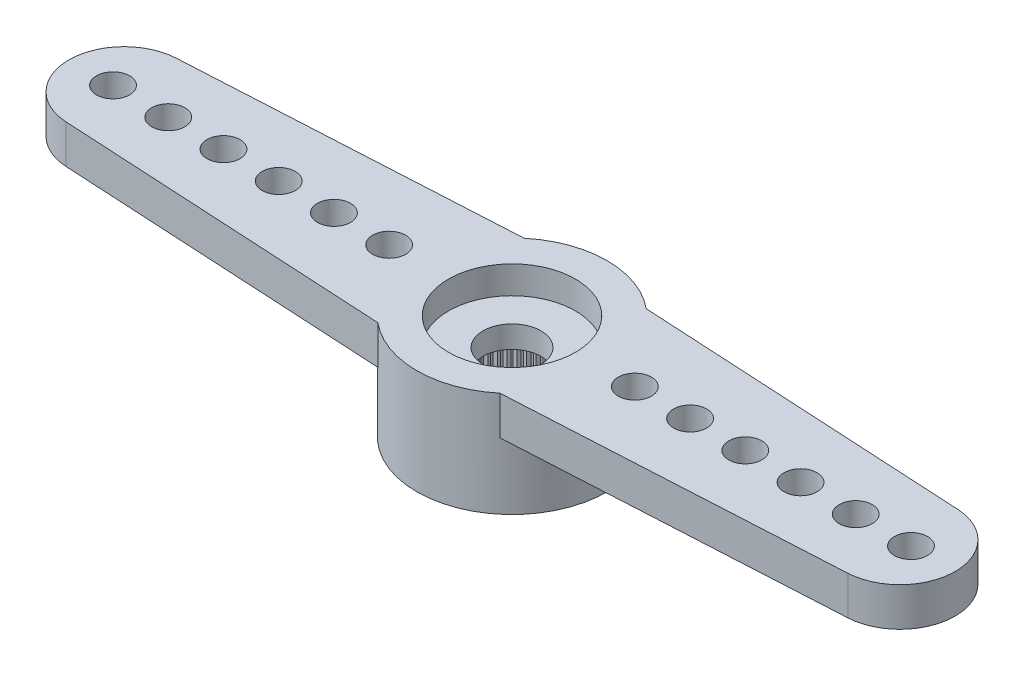
SolidWorks part; units mm, degrees
material "PVC Rígido"
ref_plane "Plano frontal" through (0, 0, 0) normal (0, 0, 1) x (1, 0, 0)
ref_plane "Plano superior" through (0, 0, 0) normal (0, 1, 0) x (1, 0, 0)
ref_plane "Plano direito" through (0, 0, 0) normal (1, 0, 0) x (0, 0, -1)
sketch "Esboço1" plane through (0, 0, 0) normal (0, 1, 0) x (1, 0, 0)
  line L0 (0, 0) -> (-14.05, 0) construction
  line L1 (-14.1591, 1.997) -> (-2.2091, 2.65)
  line L2 (-2.2091, -2.65) -> (-14.1591, -1.997)
  arc A0 (-2.2091, -2.65) -> (-2.2091, 2.65) centre (0, 0) ccw
  arc A1 (-14.1591, 1.997) -> (-14.1591, -1.997) centre (-14.05, 0) ccw
  dimension "D1" = 6.9
  dimension "D2" = 4
  dimension "D3" = 19.5
  dimension "D4" = 5.3
extrude "Ressalto-extrusão1" add sketch "Esboço1" against normal blind 1.4
sketch "Esboço2" plane through (0, -1.4, 0) normal (0, -1, 0) x (1, 0, 0)
  arc A0 (-2.2091, -2.65) -> (-2.2091, 2.65) centre (0, 0) ccw construction
  circle A1 centre (0, 0) radius 3.45
extrude "Ressalto-extrusão2" add sketch "Esboço2" along normal offset from surface (2.4 mm away) 3.8 up to face at (-7.242, 0, 0)
hole_wizard "Furo4" positions "Esboço9" profile "Esboço10" legacy end condition through all
sketch "Esboço9" plane through (0, 0, 0) normal (0, 1, 0) x (1, 0, 0)
  line L1 (-14.45, 0) -> (0, 0) construction
  arc A2 (-14.1591, 1.997) -> (-14.1591, -1.997) centre (-14.05, 0) ccw construction
  point P0 (-14.45, 0)
  point P19 (-16.05, 0)
  dimension "D1" = 1.6
sketch "Esboço10" plane through (-14.45, 0, 0) normal (1, 0, 0) x (0, 0, 1)
  line L0 (0, 0) -> (0, 3.8)
  line L1 (0, 3.8) -> (0.6, 3.8)
  line L2 (0.6, 3.8) -> (0.6, 0)
  line L3 (0.6, 0) -> (0, 0)
  line L4 (0, 110) -> (0, -10) construction
  dimension "Diameter" = 1.2
  dimension "Depth" = 3.8
pattern_linear "Padrão linear1" count 6 spacing 2 along (1, 0, 0) of "Furo4"
pattern_circular "PadrãoCircular2" count 2 over 360 about axis through (0, 0, 0) along (0, 1, 0) of "Ressalto-extrusão1", "Furo4", "Padrão linear1"
hole_wizard "Furo1" positions "Esboço3" profile "Esboço4" legacy
sketch "Esboço3" plane through (0, -3.8, 0) normal (0, -1, 0) x (-1, 0, 0)
  point P0 (0, 0)
sketch "Esboço4" plane through (0, -3.8, 0) normal (1, 0, 0) x (0, 0, -1)
  line L0 (0, 0) -> (0, 2)
  line L1 (0, 2) -> (2.475, 2)
  line L2 (2.475, 2) -> (2.475, 0)
  line L3 (2.475, 0) -> (0, 0)
  line L4 (0, 110) -> (0, -10) construction
  dimension "Diameter" = 4.95
  dimension "Depth" = 2
hole_wizard "Furo2" positions "Esboço5" profile "Esboço6" legacy
sketch "Esboço5" plane through (0, 0, 0) normal (0, 1, 0) x (1, 0, 0)
  point P0 (0, 0)
sketch "Esboço6" plane through (0, 0, 0) normal (1, 0, 0) x (0, 0, 1)
  line L0 (0, 0) -> (0, 1)
  line L1 (0, 1) -> (2.3, 1)
  line L2 (2.3, 1) -> (2.3, 0)
  line L3 (2.3, 0) -> (0, 0)
  line L4 (0, 110) -> (0, -10) construction
  dimension "Diameter" = 4.6
  dimension "Depth" = 1
hole_wizard "Furo3" positions "Esboço7" profile "Esboço8" legacy end condition through all
sketch "Esboço7" plane through (0, 0, 0) normal (0, 1, 0) x (1, 0, 0)
  point P0 (0, 0)
sketch "Esboço8" plane through (0, 0, 0) normal (1, 0, 0) x (0, 0, 1)
  line L0 (0, 0) -> (0, 3.8)
  line L1 (0, 3.8) -> (1.05, 3.8)
  line L2 (1.05, 3.8) -> (1.05, 0)
  line L3 (1.05, 0) -> (0, 0)
  line L4 (0, 110) -> (0, -10) construction
  dimension "Diameter" = 2.1
  dimension "Depth" = 3.8
sketch "Esboço11" plane through (0, -3.8, 0) normal (0, -1, 0) x (1, 0, 0)
  line L0 (-0.0981, 2.4731) -> (0, 2.375)
  line L1 (0, 2.375) -> (0.0981, 2.4731)
  line L2 (0, 0) -> (0, 2.475) construction
  circle A0 centre (0, 0) radius 2.375 construction
  circle A1 centre (0, 0) radius 2.475
  arc A2 (0.0981, 2.4731) -> (-0.0981, 2.4731) centre (0, 0) ccw
  dimension "D3" = 4.75
  dimension "D2" = 0.1
  dimension "D1" = 0
extrude "Ressalto-extrusão3" add sketch "Esboço11" against normal up to surface (2 mm away) up to face at (0, -1.8, 1.05)
pattern_circular "PadrãoCircular1" count 60 over 360 about axis through (0, 0, 0) along (0, 1, 0) of "Ressalto-extrusão3"
sketch "Sketch1" plane through (0, 0, 0) normal (0, 1, 0) x (1, 0, 0)
  line L4 (-14.1591, -1.997) -> (-2.2091, -2.65)
  line L5 (2.2091, -2.65) -> (14.1591, -1.997)
  line L6 (14.1591, 1.997) -> (2.2091, 2.65)
  line L7 (-2.2091, 2.65) -> (-14.1591, 1.997)
  line L8 (-14.1591, -1.997) -> (-2.2091, -2.65)
  line L9 (2.2091, -2.65) -> (14.1591, -1.997)
  line L10 (14.1591, 1.997) -> (2.2091, 2.65)
  line L11 (-2.2091, 2.65) -> (-14.1591, 1.997)
  circle A0 centre (-4.45, 0) radius 0.6 construction
  circle A1 centre (-6.45, 0) radius 0.6 construction
  circle A2 centre (-4.45, 0) radius 0.6
  circle A3 centre (-6.45, 0) radius 0.6
  arc A4 (-2.2091, -2.65) -> (2.2091, -2.65) centre (0, 0) ccw
  arc A5 (14.1591, -1.997) -> (14.1591, 1.997) centre (14.05, 0) ccw
  arc A6 (2.2091, 2.65) -> (-2.2091, 2.65) centre (0, 0) ccw
  arc A7 (-14.1591, 1.997) -> (-14.1591, -1.997) centre (-14.05, 0) ccw
  arc A8 (-2.2091, -2.65) -> (2.2091, -2.65) centre (0, 0) ccw
  arc A9 (14.1591, -1.997) -> (14.1591, 1.997) centre (14.05, 0) ccw
  arc A10 (2.2091, 2.65) -> (-2.2091, 2.65) centre (0, 0) ccw
  arc A11 (-14.1591, 1.997) -> (-14.1591, -1.997) centre (-14.05, 0) ccw
  circle A12 centre (-8.45, 0) radius 0.6 construction
  circle A13 centre (14.45, 0) radius 0.6 construction
  circle A14 centre (12.45, 0) radius 0.6 construction
  circle A15 centre (10.45, 0) radius 0.6 construction
  circle A16 centre (8.45, 0) radius 0.6 construction
  circle A17 centre (6.45, 0) radius 0.6 construction
  circle A18 centre (4.45, 0) radius 0.6 construction
  circle A19 centre (-14.45, 0) radius 0.6 construction
  circle A20 centre (-12.45, 0) radius 0.6 construction
  circle A21 centre (-10.45, 0) radius 0.6 construction
  circle A22 centre (14.45, 0) radius 0.6
  circle A23 centre (12.45, 0) radius 0.6
  circle A24 centre (10.45, 0) radius 0.6
  circle A25 centre (8.45, 0) radius 0.6
  circle A26 centre (6.45, 0) radius 0.6
  circle A27 centre (4.45, 0) radius 0.6
  circle A28 centre (-14.45, 0) radius 0.6
  circle A29 centre (-12.45, 0) radius 0.6
  circle A30 centre (-10.45, 0) radius 0.6
  circle A31 centre (-8.45, 0) radius 0.6
  circle A32 centre (0, 0) radius 2.3 construction
  circle A33 centre (0, 0) radius 2.3
  dimension "D1" = 0
